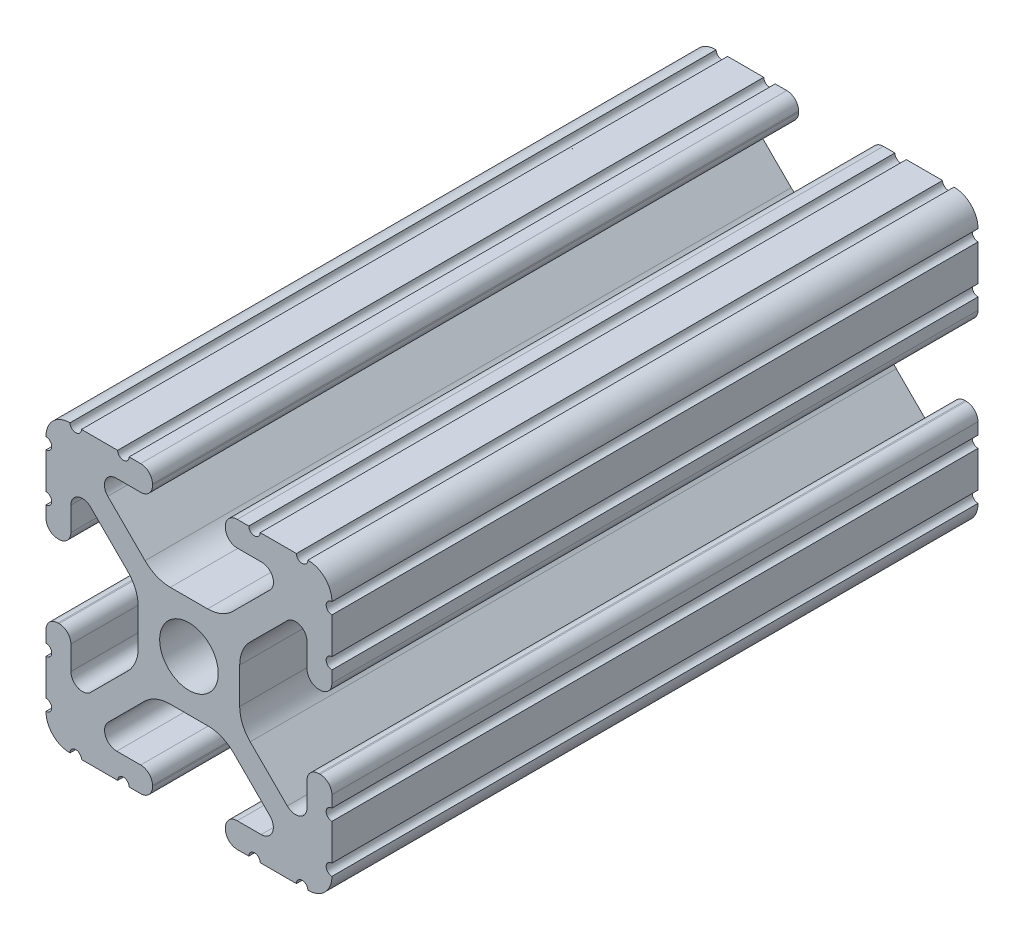
SolidWorks part; units mm, degrees
ref_plane "Front Plane" through (0, 0, 0) normal (0, 0, 1) x (1, 0, 0)
ref_plane "Top Plane" through (0, 0, 0) normal (0, 1, 0) x (1, 0, 0)
ref_plane "Right Plane" through (0, 0, 0) normal (1, 0, 0) x (0, 0, -1)
sketch "Sketch1" plane through (0, 0, 0) normal (0, 0, 1) x (1, 0, 0)
  line L88 (-7.1797, -8.6452) -> (-3.9523, -5.4237)
  line L89 (-1.7093, -4.4958) -> (1.7093, -4.4958)
  line L90 (3.9523, -5.4237) -> (7.1797, -8.6452)
  line L91 (6.4164, -10.4902) -> (4.2875, -10.4902)
  line L92 (3.2385, -11.5392) -> (3.2385, -11.651)
  line L93 (4.2875, -12.7) -> (5.3171, -12.7)
  line L94 (6.3331, -12.7) -> (9.5504, -12.7)
  line L95 (12.7, -9.5504) -> (12.7, -6.3331)
  line L96 (12.7, -5.3171) -> (12.7, -4.2875)
  line L97 (11.651, -3.2385) -> (11.5392, -3.2385)
  line L98 (10.4902, -4.2875) -> (10.4902, -6.4021)
  line L99 (8.7371, -7.1294) -> (5.441, -3.8408)
  line L100 (4.5085, -1.5932) -> (4.5085, 1.5932)
  line L101 (5.441, 3.8408) -> (8.7371, 7.1294)
  line L102 (10.4902, 6.4021) -> (10.4902, 4.2875)
  line L103 (11.5392, 3.2385) -> (11.651, 3.2385)
  line L104 (12.7, 4.2875) -> (12.7, 5.3171)
  line L105 (12.7, 6.3331) -> (12.7, 9.5504)
  line L106 (9.5504, 12.7) -> (6.3331, 12.7)
  line L107 (5.3171, 12.7) -> (4.2875, 12.7)
  line L108 (3.2385, 11.651) -> (3.2385, 11.5392)
  line L109 (4.2875, 10.4902) -> (6.4768, 10.4902)
  line L110 (7.207, 8.7244) -> (3.8983, 5.4232)
  line L111 (1.6558, 4.4958) -> (-1.6558, 4.4958)
  line L112 (-3.8983, 5.4232) -> (-7.207, 8.7244)
  line L113 (-6.4768, 10.4902) -> (-4.2875, 10.4902)
  line L114 (-3.2385, 11.5392) -> (-3.2385, 11.651)
  line L115 (-4.2875, 12.7) -> (-5.3171, 12.7)
  line L116 (-6.3331, 12.7) -> (-9.5504, 12.7)
  line L117 (-12.7, 9.5504) -> (-12.7, 6.3331)
  line L118 (-12.7, 5.3171) -> (-12.7, 4.2875)
  line L119 (-11.651, 3.2385) -> (-11.5392, 3.2385)
  line L120 (-10.4902, 4.2875) -> (-10.4902, 6.4021)
  line L121 (-8.7371, 7.1294) -> (-5.441, 3.8408)
  line L122 (-4.5085, 1.5932) -> (-4.5085, -1.5932)
  line L123 (-5.441, -3.8408) -> (-8.7371, -7.1294)
  line L124 (-10.4902, -6.4021) -> (-10.4902, -4.2875)
  line L125 (-11.5392, -3.2385) -> (-11.651, -3.2385)
  line L126 (-12.7, -4.2875) -> (-12.7, -5.3171)
  line L127 (-12.7, -6.3331) -> (-12.7, -9.5504)
  line L128 (-9.5504, -12.7) -> (-6.3331, -12.7)
  line L129 (-5.3171, -12.7) -> (-4.2875, -12.7)
  line L130 (-3.2385, -11.651) -> (-3.2385, -11.5392)
  line L131 (-4.2875, -10.4902) -> (-6.4164, -10.4902)
  circle A1 centre (0, 0) radius 2.6035
  arc A104 (-7.1797, -8.6452) -> (-6.4164, -10.4902) centre (-6.4164, -9.4098) ccw
  arc A105 (-1.7093, -4.4958) -> (-3.9523, -5.4237) centre (-1.7093, -7.6708) ccw
  arc A106 (3.9523, -5.4237) -> (1.7093, -4.4958) centre (1.7093, -7.6708) ccw
  arc A107 (6.4164, -10.4902) -> (7.1797, -8.6452) centre (6.4164, -9.4098) ccw
  arc A108 (4.2875, -10.4902) -> (3.2385, -11.5392) centre (4.2875, -11.5392) ccw
  arc A109 (3.2385, -11.651) -> (4.2875, -12.7) centre (4.2875, -11.651) ccw
  arc A110 (6.3331, -12.7) -> (5.3171, -12.7) centre (5.8251, -12.7) ccw
  arc A111 (10.5664, -12.6998) -> (9.5504, -12.7) centre (10.0584, -12.7) ccw
  arc A112 (10.5664, -12.6998) -> (12.6998, -10.5664) centre (10.5918, -10.5918) ccw
  arc A113 (12.7, -9.5504) -> (12.6998, -10.5664) centre (12.7, -10.0584) ccw
  arc A114 (12.7, -5.3171) -> (12.7, -6.3331) centre (12.7, -5.8251) ccw
  arc A115 (12.7, -4.2875) -> (11.651, -3.2385) centre (11.651, -4.2875) ccw
  arc A116 (11.5392, -3.2385) -> (10.4902, -4.2875) centre (11.5392, -4.2875) ccw
  arc A117 (8.7371, -7.1294) -> (10.4902, -6.4021) centre (9.4628, -6.4021) ccw
  arc A118 (4.5085, -1.5932) -> (5.441, -3.8408) centre (7.6835, -1.5932) ccw
  arc A119 (5.441, 3.8408) -> (4.5085, 1.5932) centre (7.6835, 1.5932) ccw
  arc A120 (10.4902, 6.4021) -> (8.7371, 7.1294) centre (9.4628, 6.4021) ccw
  arc A121 (10.4902, 4.2875) -> (11.5392, 3.2385) centre (11.5392, 4.2875) ccw
  arc A122 (11.651, 3.2385) -> (12.7, 4.2875) centre (11.651, 4.2875) ccw
  arc A123 (12.7, 6.3331) -> (12.7, 5.3171) centre (12.7, 5.8251) ccw
  arc A124 (12.6998, 10.5664) -> (12.7, 9.5504) centre (12.7, 10.0584) ccw
  arc A125 (12.6998, 10.5664) -> (10.5664, 12.6998) centre (10.5918, 10.5918) ccw
  arc A126 (9.5504, 12.7) -> (10.5664, 12.6998) centre (10.0584, 12.7) ccw
  arc A127 (5.3171, 12.7) -> (6.3331, 12.7) centre (5.8251, 12.7) ccw
  arc A128 (4.2875, 12.7) -> (3.2385, 11.651) centre (4.2875, 11.651) ccw
  arc A129 (3.2385, 11.5392) -> (4.2875, 10.4902) centre (4.2875, 11.5392) ccw
  arc A130 (7.207, 8.7244) -> (6.4768, 10.4902) centre (6.4768, 9.4563) ccw
  arc A131 (1.6558, 4.4958) -> (3.8983, 5.4232) centre (1.6558, 7.6708) ccw
  arc A132 (-3.8983, 5.4232) -> (-1.6558, 4.4958) centre (-1.6558, 7.6708) ccw
  arc A133 (-6.4768, 10.4902) -> (-7.207, 8.7244) centre (-6.4768, 9.4563) ccw
  arc A134 (-4.2875, 10.4902) -> (-3.2385, 11.5392) centre (-4.2875, 11.5392) ccw
  arc A135 (-3.2385, 11.651) -> (-4.2875, 12.7) centre (-4.2875, 11.651) ccw
  arc A136 (-6.3331, 12.7) -> (-5.3171, 12.7) centre (-5.8251, 12.7) ccw
  arc A137 (-10.5664, 12.6998) -> (-9.5504, 12.7) centre (-10.0584, 12.7) ccw
  arc A138 (-10.5664, 12.6998) -> (-12.6998, 10.5664) centre (-10.5918, 10.5918) ccw
  arc A139 (-12.7, 9.5504) -> (-12.6998, 10.5664) centre (-12.7, 10.0584) ccw
  arc A140 (-12.7, 5.3171) -> (-12.7, 6.3331) centre (-12.7, 5.8251) ccw
  arc A141 (-12.7, 4.2875) -> (-11.651, 3.2385) centre (-11.651, 4.2875) ccw
  arc A142 (-11.5392, 3.2385) -> (-10.4902, 4.2875) centre (-11.5392, 4.2875) ccw
  arc A143 (-8.7371, 7.1294) -> (-10.4902, 6.4021) centre (-9.4628, 6.4021) ccw
  arc A144 (-4.5085, 1.5932) -> (-5.441, 3.8408) centre (-7.6835, 1.5932) ccw
  arc A145 (-5.441, -3.8408) -> (-4.5085, -1.5932) centre (-7.6835, -1.5932) ccw
  arc A146 (-10.4902, -6.4021) -> (-8.7371, -7.1294) centre (-9.4628, -6.4021) ccw
  arc A147 (-10.4902, -4.2875) -> (-11.5392, -3.2385) centre (-11.5392, -4.2875) ccw
  arc A148 (-11.651, -3.2385) -> (-12.7, -4.2875) centre (-11.651, -4.2875) ccw
  arc A149 (-12.7, -6.3331) -> (-12.7, -5.3171) centre (-12.7, -5.8251) ccw
  arc A150 (-12.6998, -10.5664) -> (-12.7, -9.5504) centre (-12.7, -10.0584) ccw
  arc A151 (-12.6998, -10.5664) -> (-10.5664, -12.6998) centre (-10.5918, -10.5918) ccw
  arc A152 (-9.5504, -12.7) -> (-10.5664, -12.6998) centre (-10.0584, -12.7) ccw
  arc A153 (-5.3171, -12.7) -> (-6.3331, -12.7) centre (-5.8251, -12.7) ccw
  arc A154 (-4.2875, -12.7) -> (-3.2385, -11.651) centre (-4.2875, -11.651) ccw
  arc A155 (-3.2385, -11.5392) -> (-4.2875, -10.4902) centre (-4.2875, -11.5392) ccw
extrude "Boss-Extrude1" add sketch "Sketch1" along normal mid plane 304.8
sketch "Sketch2" plane through (0, 0, 152.4) normal (0, 0, 1) x (1, 0, 0)
  circle A0 centre (0, 0) radius 23.9419
extrude "Cut-Extrude1" cut sketch "Sketch2" against normal blind 247.396
